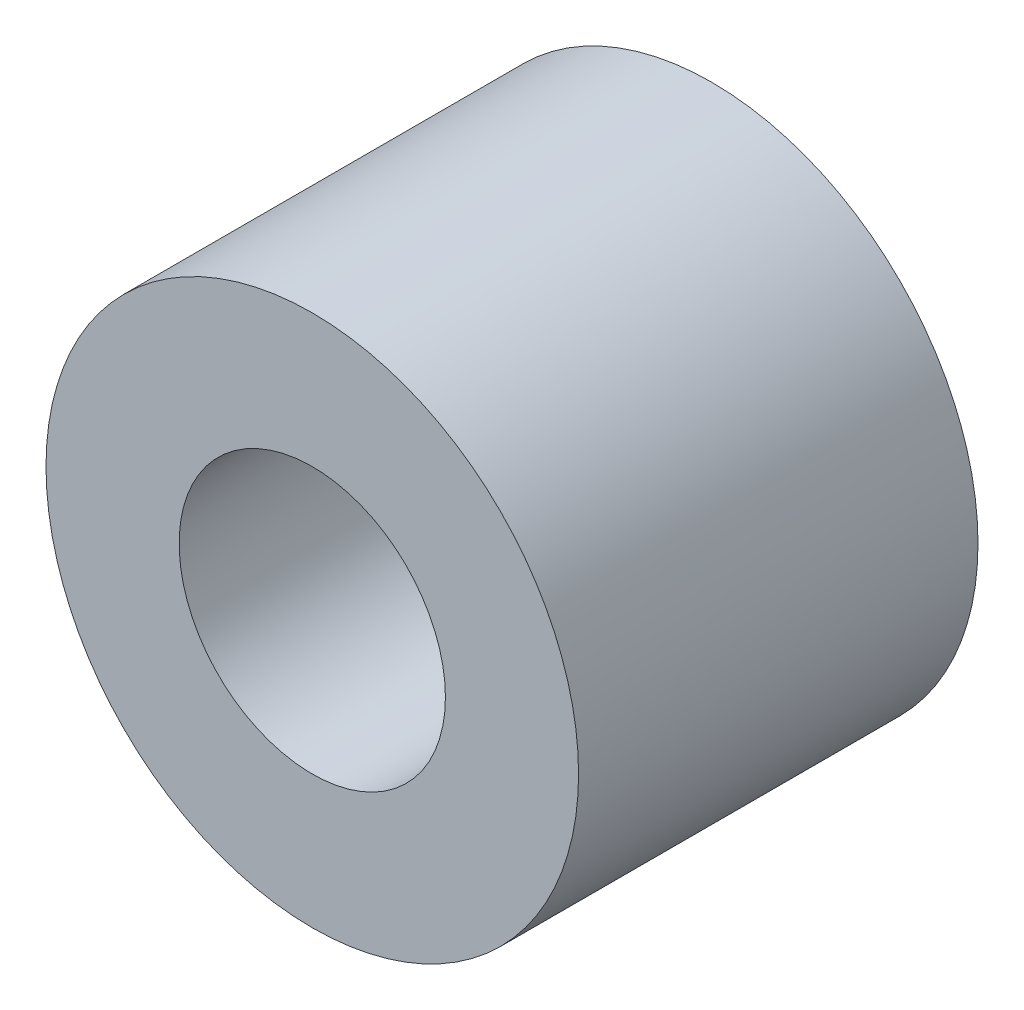
SolidWorks part; units mm, degrees
ref_plane "前视基准面" through (0, 0, 0) normal (0, 0, 1) x (1, 0, 0)
ref_plane "上视基准面" through (0, 0, 0) normal (0, 1, 0) x (1, 0, 0)
ref_plane "右视基准面" through (0, 0, 0) normal (1, 0, 0) x (0, 0, -1)
sketch "草图1" plane through (0, 0, 0) normal (0, 0, 1) x (1, 0, 0)
  circle A0 centre (0, 0) radius 4.5
  circle A1 centre (0, 0) radius 2.25
  dimension "D1" = 4.5
  dimension "D2" = 9
extrude "凸台-拉伸1" add sketch "草图1" along normal blind 6.75
